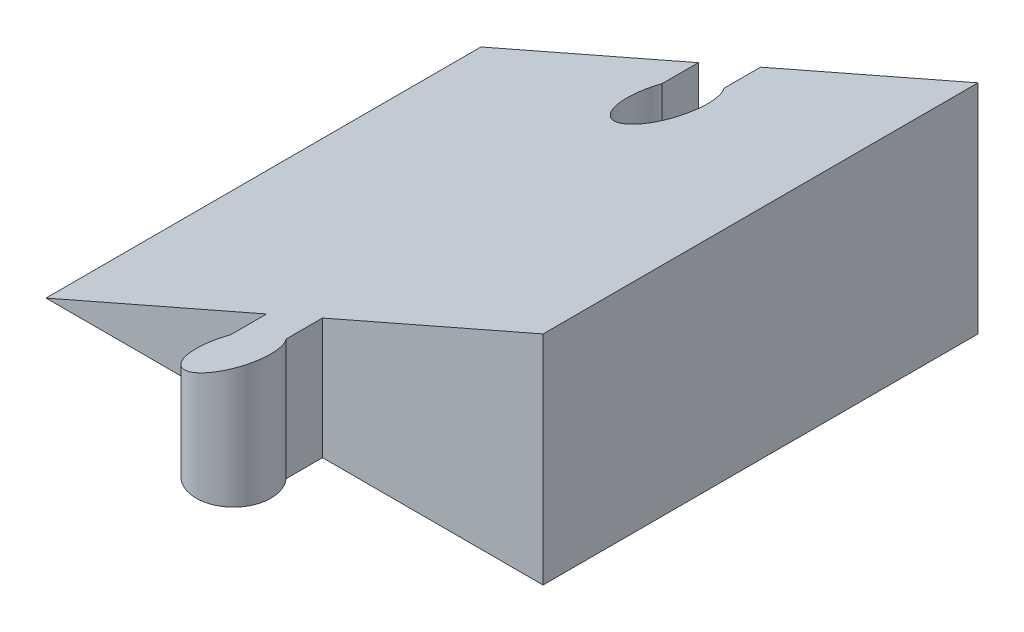
SolidWorks part; units mm, degrees
ref_plane "Front Plane" through (0, 0, 0) normal (0, 0, 1) x (1, 0, 0)
ref_plane "Top Plane" through (0, 0, 0) normal (0, 1, 0) x (1, 0, 0)
ref_plane "Right Plane" through (0, 0, 0) normal (1, 0, 0) x (0, 0, -1)
sketch "Esboço1" plane through (0, 0, 0) normal (0, 0, 1) x (1, 0, 0)
  line L0 (-46.1667, -15.6528) -> (33.8333, 19.3472)
  line L3 (-46.1667, -15.6528) -> (33.8333, -15.6528)
  line L4 (33.8333, 19.3472) -> (33.8333, -15.6528)
  dimension "D1" = 35
  dimension "D2" = 80
extrude "Ressalto-extrusão1" add sketch "Esboço1" along normal blind 70
sketch "Esboço2" plane through (0, -15.6528, 0) normal (0, -1, 0) x (1, 0, 0)
  line L0 (33.8333, 35) -> (-46.1667, 35) construction
  line L1 (33.8333, 70) -> (33.8333, 0) construction
  line L2 (-46.1667, 70) -> (-46.1667, 0) construction
  line L3 (-6.1667, 0) -> (-6.1667, 3.5) construction
  line L4 (-46.1667, 0) -> (33.8333, 0) construction
  line L5 (-46.1667, 70) -> (33.8333, 70) construction
  line L6 (-6.1667, 10) -> (-6.1667, 70) construction
  line L7 (-11.1667, 0) -> (-1.1667, 0)
  line L8 (-11.1667, 0) -> (-11.1667, 5.8467)
  line L10 (-1.1667, 0) -> (-1.1667, 5.8467)
  arc A0 (-1.1667, 5.8467) -> (-11.1667, 5.8467) centre (-6.1667, 10) ccw
  point P16 (-6.1667, 0)
  point P19 (0, 0)
  dimension "D3" = 13
  dimension "D1" = 5
sketch "Esboço3" plane through (0, -15.6528, 0) normal (0, -1, 0) x (1, 0, 0)
  line L0 (-6.1667, 70) -> (-6.1667, 73.5) construction
  line L1 (-10.6667, 70) -> (-1.6667, 70)
  line L2 (-10.6667, 70) -> (-10.6667, 75.8467)
  line L3 (-1.6667, 70) -> (-1.6667, 75.8467)
  arc A0 (-1.6667, 75.8467) -> (-10.6667, 75.8467) centre (-6.1667, 79.8153) ccw
  point P4 (-6.1667, 70)
  point P8 (0, 0)
  dimension "D2" = 6
  dimension "D1" = 4.5
extrude "Ressalto-extrusão2" add sketch "Esboço3" against normal up to surface (15.5313 mm away)
extrude "Corte-extrusão1" cut sketch "Esboço2" against normal blind 70
